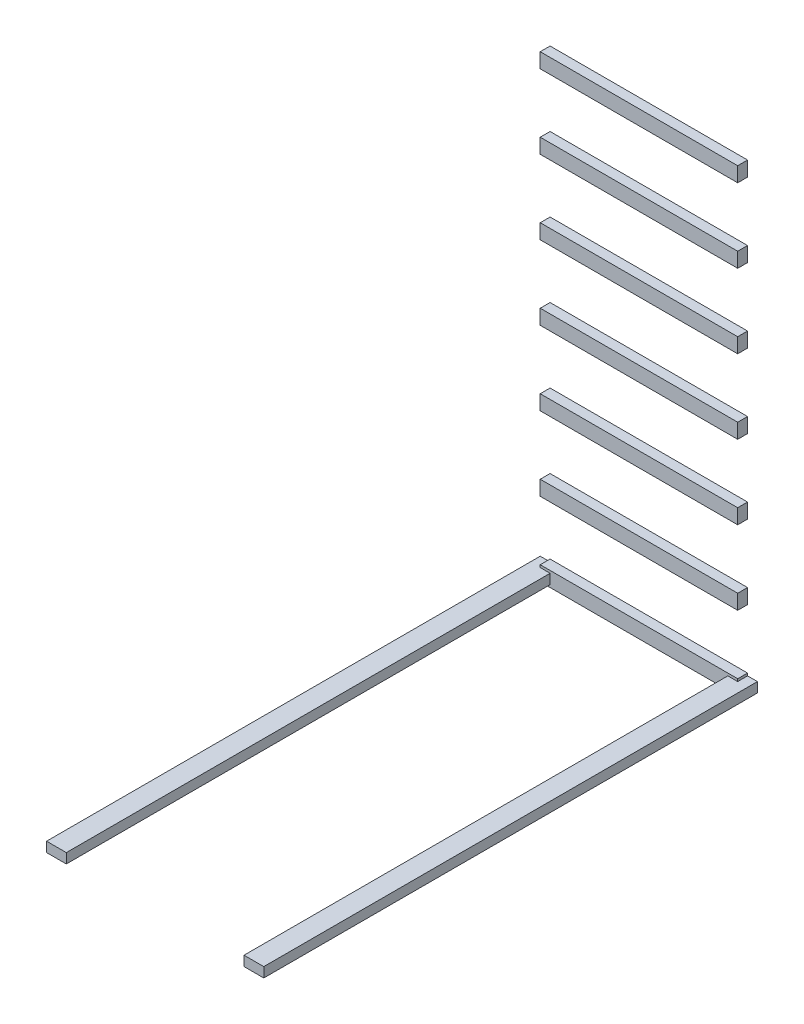
SolidWorks part; units mm, degrees
ref_plane "前视基准面" through (0, 0, 0) normal (0, 0, 1) x (1, 0, 0)
ref_plane "上视基准面" through (0, 0, 0) normal (0, 1, 0) x (1, 0, 0)
ref_plane "右视基准面" through (0, 0, 0) normal (1, 0, 0) x (0, 0, -1)
other "Configuration Table"
sketch "草图1" plane through (0, 0, 0) normal (0, 0, 1) x (1, 0, 0)
  line L1 (-440, -20) -> (-360, -20)
  line L2 (-440, -20) -> (-440, 20)
  line L3 (-440, 20) -> (-360, 20)
  line L4 (-360, -20) -> (-360, 20)
  line L5 (-440, -20) -> (-360, 20) construction
  line L6 (-440, 20) -> (-360, -20) construction
  point P0 (-400, 0)
extrude "凸台-拉伸1" add sketch "草图1" along normal blind 2000
sketch "草图2" plane through (0, 0, 0) normal (0, 0, 1) x (1, 0, 0)
  line L1 (360, -20) -> (440, -20)
  line L2 (360, -20) -> (360, 20)
  line L3 (360, 20) -> (440, 20)
  line L4 (440, -20) -> (440, 20)
  line L5 (360, -20) -> (440, 20) construction
  line L6 (360, 20) -> (440, -20) construction
  point P0 (400, 0)
extrude "凸台-拉伸2" add sketch "草图2" along normal blind 2000
sketch "草图3" plane through (0, 0, 0) normal (0, 0, 1) x (1, 0, 0)
  line L1 (-400, -30) -> (400, -30)
  line L2 (-400, -30) -> (-400, 30)
  line L3 (-400, 30) -> (400, 30)
  line L4 (400, -30) -> (400, 30)
  line L5 (-400, -30) -> (400, 30) construction
  line L6 (-400, 30) -> (400, -30) construction
  point P0 (0, 0)
extrude "凸台-拉伸3" add sketch "草图3" along normal blind 40
sketch "草图4" plane through (0, 0, 0) normal (0, 0, 1) x (1, 0, 0)
  line L1 (-400, 270) -> (400, 270)
  line L2 (-400, 270) -> (-400, 330)
  line L3 (-400, 330) -> (400, 330)
  line L4 (400, 270) -> (400, 330)
  line L5 (-400, 270) -> (400, 330) construction
  line L6 (-400, 330) -> (400, 270) construction
  point P0 (0, 300)
extrude "凸台-拉伸4" add sketch "草图4" along normal blind 40
sketch "草图5" plane through (0, 0, 0) normal (0, 0, 1) x (1, 0, 0)
  line L1 (-400, 570) -> (400, 570)
  line L2 (-400, 570) -> (-400, 630)
  line L3 (-400, 630) -> (400, 630)
  line L4 (400, 570) -> (400, 630)
  line L5 (-400, 570) -> (400, 630) construction
  line L6 (-400, 630) -> (400, 570) construction
  point P0 (0, 600)
extrude "凸台-拉伸5" add sketch "草图5" along normal blind 40
sketch "草图6" plane through (0, 0, 0) normal (0, 0, 1) x (1, 0, 0)
  line L1 (-400, 870) -> (400, 870)
  line L2 (-400, 870) -> (-400, 930)
  line L3 (-400, 930) -> (400, 930)
  line L4 (400, 870) -> (400, 930)
  line L5 (-400, 870) -> (400, 930) construction
  line L6 (-400, 930) -> (400, 870) construction
  point P0 (0, 900)
extrude "凸台-拉伸6" add sketch "草图6" along normal blind 40
sketch "草图7" plane through (0, 0, 0) normal (0, 0, 1) x (1, 0, 0)
  line L1 (-400, 1170) -> (400, 1170)
  line L2 (-400, 1170) -> (-400, 1230)
  line L3 (-400, 1230) -> (400, 1230)
  line L4 (400, 1170) -> (400, 1230)
  line L5 (-400, 1170) -> (400, 1230) construction
  line L6 (-400, 1230) -> (400, 1170) construction
  point P0 (0, 1200)
extrude "凸台-拉伸7" add sketch "草图7" along normal blind 40
sketch "草图8" plane through (0, 0, 0) normal (0, 0, 1) x (1, 0, 0)
  line L1 (-400, 1470) -> (400, 1470)
  line L2 (-400, 1470) -> (-400, 1530)
  line L3 (-400, 1530) -> (400, 1530)
  line L4 (400, 1470) -> (400, 1530)
  line L5 (-400, 1470) -> (400, 1530) construction
  line L6 (-400, 1530) -> (400, 1470) construction
  point P0 (0, 1500)
extrude "凸台-拉伸8" add sketch "草图8" along normal blind 40
sketch "草图9" plane through (0, 0, 0) normal (0, 0, 1) x (1, 0, 0)
  line L1 (-400, 1770) -> (400, 1770)
  line L2 (-400, 1770) -> (-400, 1830)
  line L3 (-400, 1830) -> (400, 1830)
  line L4 (400, 1770) -> (400, 1830)
  line L5 (-400, 1770) -> (400, 1830) construction
  line L6 (-400, 1830) -> (400, 1770) construction
  point P0 (0, 1800)
extrude "凸台-拉伸9" add sketch "草图9" along normal blind 40
